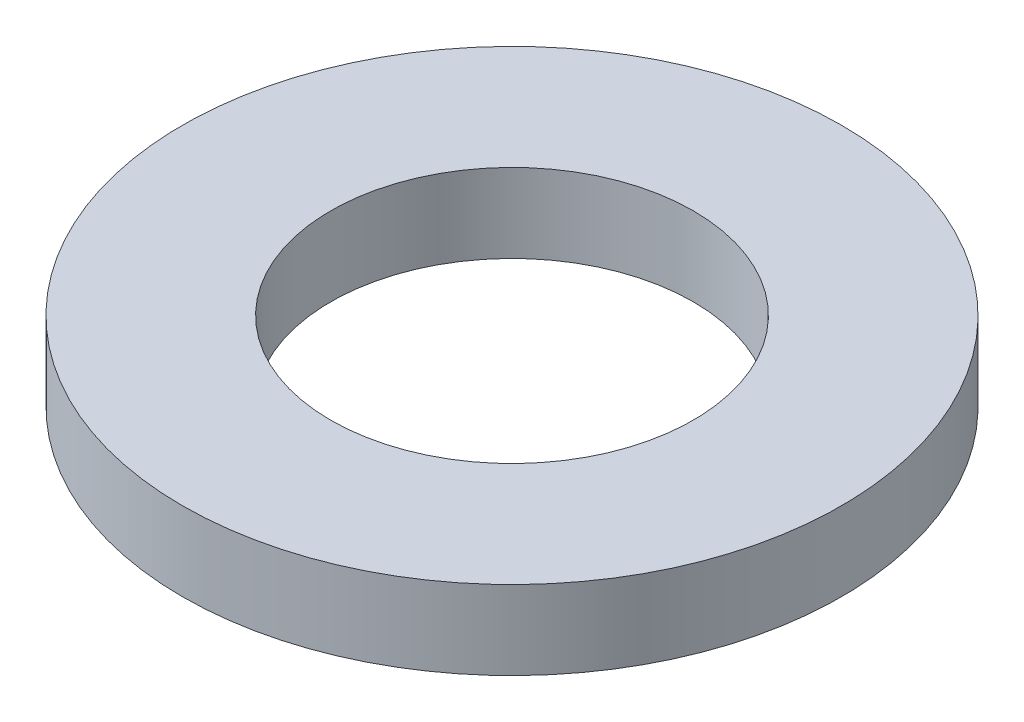
SolidWorks part; units mm, degrees
material "Cast Stainless Steel"
ref_plane "Front Plane" through (0, 0, 0) normal (0, 0, 1) x (1, 0, 0)
ref_plane "Top Plane" through (0, 0, 0) normal (0, 1, 0) x (1, 0, 0)
ref_plane "Right Plane" through (0, 0, 0) normal (1, 0, 0) x (0, 0, -1)
sketch "Sketch1" plane through (0, 0, 0) normal (0, 1, 0) x (1, 0, 0)
  circle A0 centre (0, 0) radius 1.4605
  circle A1 centre (0, 0) radius 2.6543
extrude "Boss-Extrude1" add sketch "Sketch1" along normal blind 0.635
